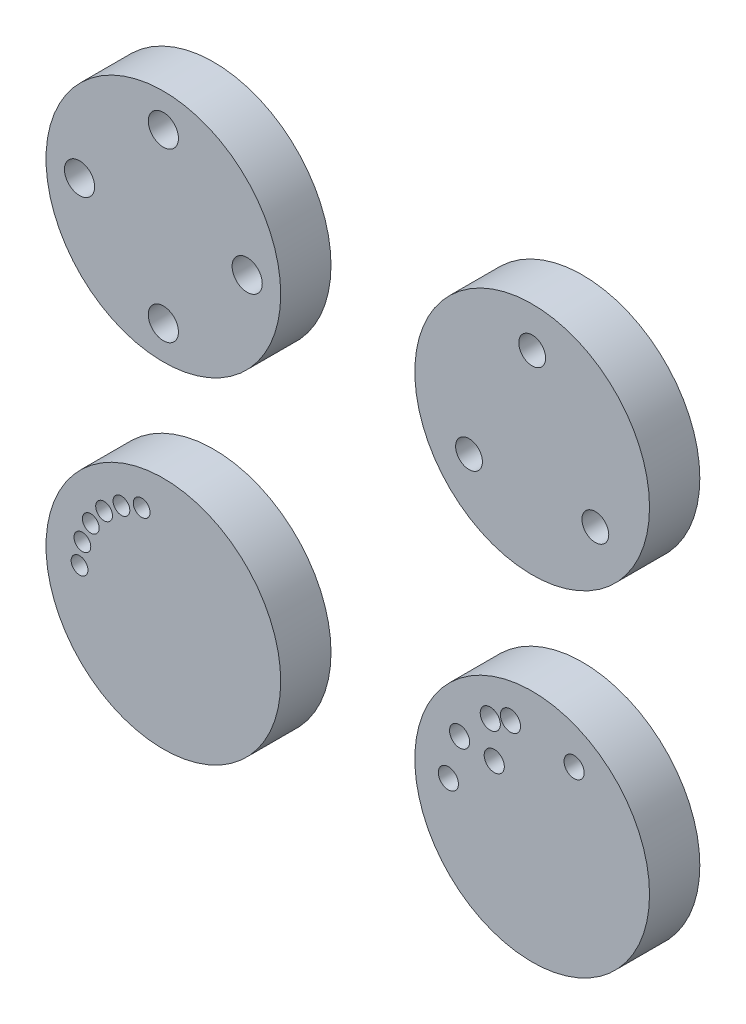
SolidWorks part; units mm, degrees
material "Сталь"
ref_plane "Спереди" through (0, 0, 0) normal (0, 0, 1) x (1, 0, 0)
ref_plane "Сверху" through (0, 0, 0) normal (0, 1, 0) x (1, 0, 0)
ref_plane "Справа" through (0, 0, 0) normal (1, 0, 0) x (0, 0, -1)
sketch "Эскиз1" plane through (0, 0, 0) normal (0, 0, 1) x (1, 0, 0)
  circle A0 centre (0, 0) radius 35
  dimension "D1" = 70
extrude "Бобышка-Вытянуть1" add sketch "Эскиз1" along normal blind 15
sketch "Эскиз2" plane through (0, 0, 15) normal (0, 0, 1) x (1, 0, 0)
  line L0 (0, 0) -> (0, 35) construction
  circle A0 centre (0, 0) radius 35 construction
  circle A1 centre (0, 25) radius 4.5
  dimension "D1" = 9
  dimension "D2" = 25
extrude "Вырез-Вытянуть1" cut sketch "Эскиз2" against normal through all
pattern_circular "Круговой массив1" count 4 over 360 about axis through (0, 0, 0) along (0, 0, 1) of "Вырез-Вытянуть1"
sketch "Эскиз3" plane through (0, 0, 0) normal (0, 0, 1) x (1, 0, 0)
  circle A0 centre (110, 0) radius 35
  circle A1 centre (0, 0) radius 35 construction
  dimension "D1" = 110
extrude "Бобышка-Вытянуть2" add sketch "Эскиз3" along normal blind 15 separate body
sketch "Эскиз4" plane through (0, 0, 15) normal (0, 0, 1) x (1, 0, 0)
  line L0 (110, 35) -> (110, -35) construction
  line L1 (75, 0) -> (145, 0) construction
  line L2 (110, 0) -> (128.8405, -13.1923) construction
  line L3 (110, 0) -> (91.1595, -13.1923) construction
  line L4 (87.3494, 3.9939) -> (110, 0) construction
  circle A0 centre (110, 0) radius 35 construction
  circle A1 centre (110, 23) radius 4
  circle A2 centre (110, 0) radius 23
  circle A3 centre (128.8405, -13.1923) radius 4
  circle A4 centre (91.1595, -13.1923) radius 4
  dimension "D1" = 8
  dimension "D2" = 46
  dimension "D5" = 45
  dimension "D3" = 125
  dimension "D4" = 110
extrude "Вырез-Вытянуть2" cut sketch "Эскиз4" against normal blind 15 contours A2 A1 | A1 A2 | A2 A4 | A2 A4 | A2 A3 | A2 A3
sketch "Эскиз5" plane through (0, 0, 0) normal (0, 0, 1) x (1, 0, 0)
  circle A0 centre (0, -100) radius 35
  circle A1 centre (0, 0) radius 35 construction
  dimension "D1" = 100
extrude "Бобышка-Вытянуть3" add sketch "Эскиз5" along normal blind 15 separate body
sketch "Эскиз6" plane through (0, 0, 15) normal (0, 0, 1) x (1, 0, 0)
  line L0 (0, -65) -> (0, -135) construction
  line L1 (-35, -100) -> (35, -100) construction
  circle A0 centre (0, -100) radius 35 construction
  circle A1 centre (-25, -100) radius 2.5
  circle A2 centre (0, -100) radius 25
  dimension "D1" = 5
  dimension "D2" = 50
extrude "Вырез-Вытянуть3" cut sketch "Эскиз6" against normal blind 10 contours A1 A2
pattern_circular "Круговой массив2" count 6 every 15 about axis through (0, -100, 0) along (0, 0, 1) of "Вырез-Вытянуть3"
sketch "Эскиз7" plane through (0, 0, 0) normal (0, 0, 1) x (1, 0, 0)
  line L0 (0, 0) -> (0, -100) construction
  line L3 (110, 0) -> (0, 0) construction
  circle A0 centre (110, -100) radius 35
  circle A1 centre (0, -100) radius 35 construction
extrude "Бобышка-Вытянуть4" add sketch "Эскиз7" along normal blind 15 separate body
sketch "Эскиз8" plane through (0, 0, 15) normal (0, 0, 1) x (1, 0, 0)
  line L0 (75, -100) -> (110, -100) construction
  line L1 (110, -100) -> (110, -65) construction
  line L2 (88.3494, -87.5) -> (110, -100) construction
  line L3 (98.6863, -88.6863) -> (110, -100) construction
  line L4 (97.5, -78.3494) -> (110, -100) construction
  line L5 (103.5295, -75.8519) -> (110, -100) construction
  line L6 (122.5, -78.3494) -> (110, -100) construction
  circle A0 centre (110, -100) radius 35 construction
  circle A1 centre (85, -100) radius 3
  circle A2 centre (110, -100) radius 25
  circle A3 centre (88.3494, -87.5) radius 3
  circle A4 centre (97.5, -78.3494) radius 3
  circle A5 centre (103.5295, -75.8519) radius 3
  circle A6 centre (98.6863, -88.6863) radius 3
  circle A7 centre (122.5, -78.3494) radius 3
  dimension "D1" = 6
  dimension "D2" = 50
  dimension "D6" = 16
  dimension "D3" = 30
  dimension "D4" = 45
  dimension "D5" = 60
  dimension "D7" = 75
  dimension "D8" = 120
extrude "Вырез-Вытянуть4" cut sketch "Эскиз8" against normal blind 10 contours A6 | A2 A3 | A2 A3 | A2 A1 | A1 A2 | A2 A4 | A2 A4 | A2 A5 | A2 A5 | A2 A7 | A2 A7
